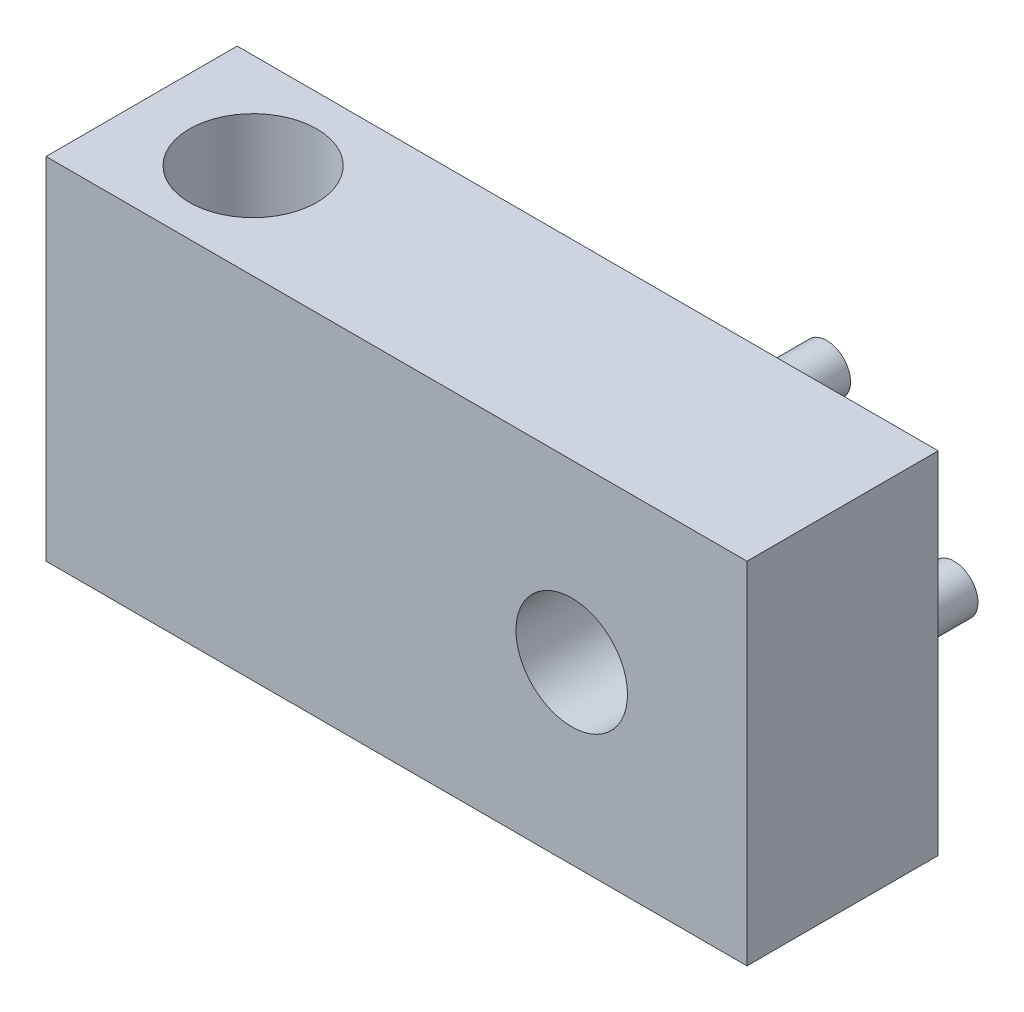
SolidWorks part; units mm, degrees
ref_plane "前视基准面" through (0, 0, 0) normal (0, 0, 1) x (1, 0, 0)
ref_plane "上视基准面" through (0, 0, 0) normal (0, 1, 0) x (1, 0, 0)
ref_plane "右视基准面" through (0, 0, 0) normal (1, 0, 0) x (0, 0, -1)
sketch "草图1" plane through (0, 0, 0) normal (0, 0, 1) x (1, 0, 0)
  line L1 (-11, 11) -> (11, 11)
  line L2 (-11, 11) -> (-11, -11)
  line L3 (-11, -11) -> (11, -11)
  line L4 (11, 11) -> (11, -11)
  line L5 (-11, 11) -> (11, -11) construction
  line L6 (-11, -11) -> (11, 11) construction
  point P0 (0, 0)
  dimension "D1" = 22
  dimension "D2" = 22
extrude "凸台-拉伸1" add sketch "草图1" along normal blind 12
sketch "草图3" plane through (0, 0, 12) normal (0, 0, 1) x (1, 0, 0)
  circle A0 centre (0, 0) radius 3.5
  dimension "D1" = 7
extrude "切除-拉伸2" cut sketch "草图3" against normal blind 12 contours A0
sketch "草图5" plane through (0, 0, 0) normal (0, 0, -1) x (-1, 0, 0)
  line L0 (0, 0) -> (0, 8) construction
  circle A0 centre (0, 0) radius 8 construction
  circle A1 centre (0, 8) radius 1.5
  circle A2 centre (8, 0) radius 1.5
  circle A3 centre (0, -8) radius 1.5
  circle A4 centre (-8, 0) radius 1.5
  point P14 (0, 0)
  dimension "D1" = 16
  dimension "D2" = 4
extrude "凸台-拉伸2" add sketch "草图5" along normal blind 4
sketch "草图6" plane through (-11, 0, 0) normal (-1, 0, 0) x (0, 0, 1)
  line L4 (0, 11) -> (0, -11)
  line L5 (0, -11) -> (12, -11)
  line L6 (12, -11) -> (12, 11)
  line L7 (12, 11) -> (0, 11)
  line L8 (0, 11) -> (0, -11)
  line L9 (0, -11) -> (12, -11)
  line L10 (12, -11) -> (12, 11)
  line L11 (12, 11) -> (0, 11)
  dimension "D1" = 0
extrude "凸台-拉伸3" add sketch "草图6" along normal blind 22
sketch "草图7" plane through (0, -11, 0) normal (0, -1, 0) x (1, 0, 0)
  line L0 (-26, 12) -> (-26, 0) construction
  line L1 (-33, 12) -> (11, 12) construction
  line L2 (-33, 0) -> (11, 0) construction
  circle A0 centre (-26, 6) radius 4
  dimension "D2" = 8
  dimension "D1" = 26
  dimension "D3" = 12
extrude "切除-拉伸3" cut sketch "草图7" against normal blind 22
